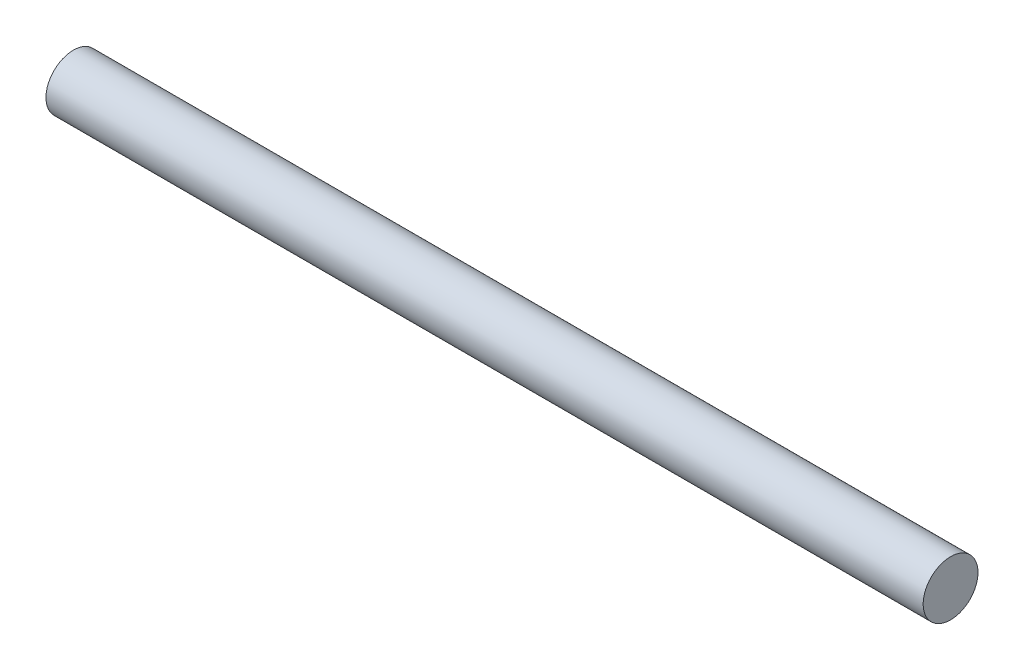
SolidWorks part; units mm, degrees
ref_plane "Front Plane" through (0, 0, 0) normal (1, 0, 0) x (0, 1, 0)
ref_plane "Top Plane" through (0, 0, 0) normal (0, 0, 1) x (0, 1, 0)
ref_plane "Right Plane" through (0, 0, 0) normal (0, 1, 0) x (-1, 0, 0)
sketch "Sketch1" plane through (0, 0, 0) normal (1, 0, 0) x (0, 1, 0)
  circle A0 centre (0, 0) radius 3.175
  dimension "D1" = 6.35
extrude "Boss-Extrude1" add sketch "Sketch1" along normal blind 101.6
